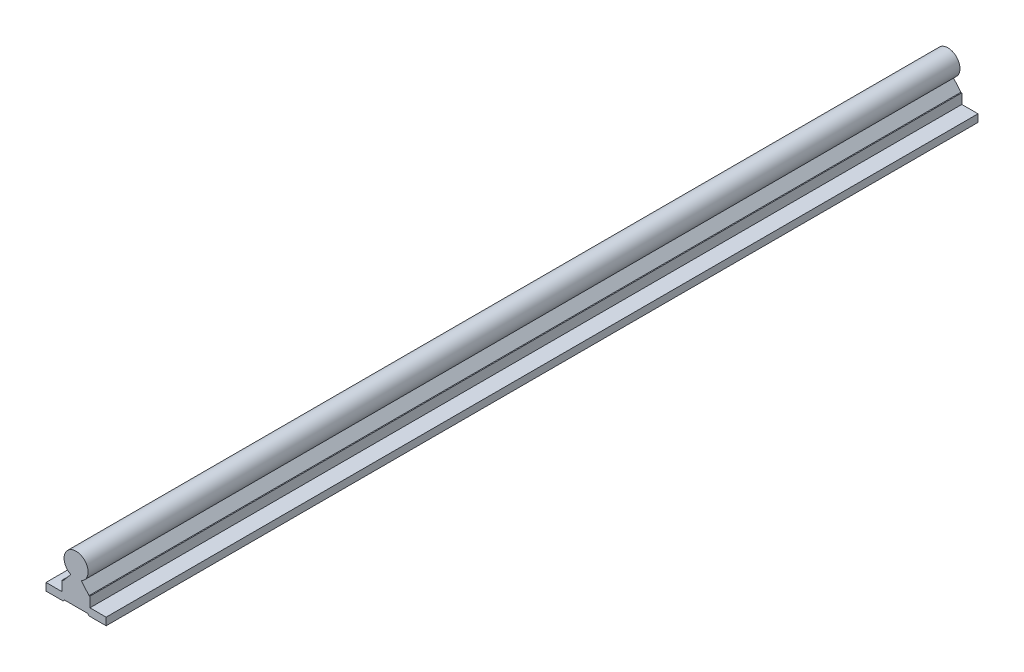
SolidWorks part; units mm, degrees
material "1.0037 (S235JR)"
ref_plane "Płaszczyzna przednia" through (0, 0, 0) normal (0, 0, 1) x (1, 0, 0)
ref_plane "Płaszczyzna górna" through (0, 0, 0) normal (0, 1, 0) x (1, 0, 0)
ref_plane "Płaszczyzna prawa" through (0, 0, 0) normal (1, 0, 0) x (0, 0, -1)
sketch "Szkic1" plane through (0, 0, 0) normal (0, 0, 1) x (1, 0, 0)
  line L0 (0, 0) -> (0, 33) construction
  line L1 (-3.4871, 17.8) -> (-8.6056, 11.7)
  line L2 (-8.6056, 11.7) -> (-9.25, 11.7)
  line L3 (-9.25, 11.7) -> (-9.25, 5)
  line L4 (-9.25, 5) -> (-20, 5)
  line L5 (-20, 5) -> (-20, 0)
  line L6 (-20, 0) -> (-8.6056, 0)
  line L7 (-8.6056, 0) -> (-7.7665, 1)
  line L8 (-7.7665, 1) -> (7.7665, 1)
  line L9 (8.6056, 0) -> (7.7665, 1)
  line L10 (20, 0) -> (8.6056, 0)
  line L11 (20, 5) -> (20, 0)
  line L12 (9.25, 5) -> (20, 5)
  line L13 (9.25, 11.7) -> (9.25, 5)
  line L14 (8.6056, 11.7) -> (9.25, 11.7)
  line L15 (3.4871, 17.8) -> (8.6056, 11.7)
  arc A0 (3.4871, 17.8) -> (-3.4871, 17.8) centre (0, 25) ccw
  point P15 (0, 1)
  dimension "D1" = 1
  dimension "D" = 16
  dimension "W" = 40
  dimension "J" = 18.5
  dimension "O" = 80
  dimension "T" = 5
  dimension "K" = 11.7
  dimension "F" = 17.8
  dimension "H" = 25
extrude "Dodanie-wyciągnięcie1" add sketch "Szkic1" along normal blind 580
sketch "Szkic2" plane through (0, 0, 0) normal (0, -1, 0) x (1, 0, 0)
  line L0 (0, 0) -> (0, 580) construction
  line L1 (-7.7665, 580) -> (7.7665, 580) construction
